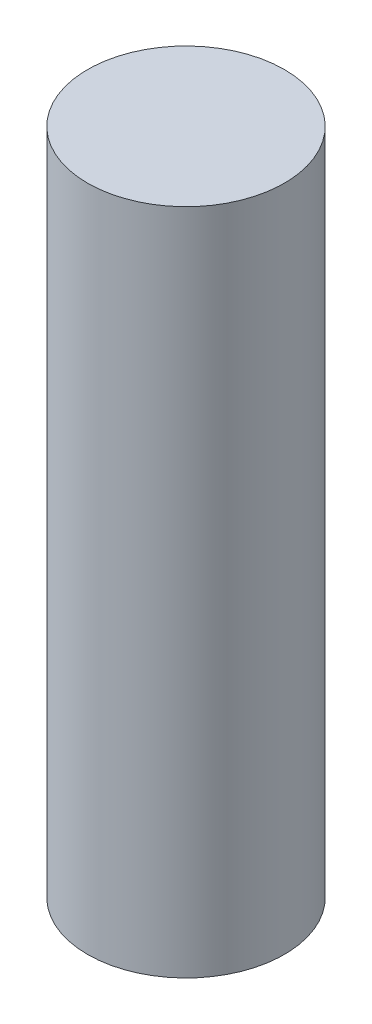
SolidWorks part; units mm, degrees
ref_plane "Front" through (0, 0, 0) normal (0, 0, 1) x (1, 0, 0)
ref_plane "Top" through (0, 0, 0) normal (0, 1, 0) x (1, 0, 0)
ref_plane "Right" through (0, 0, 0) normal (1, 0, 0) x (0, 0, -1)
sketch "Sketch1" plane through (0, 0, 0) normal (0, 1, 0) x (1, 0, 0)
  circle A0 centre (0, 0) radius 1.4
  dimension "D1" = 2.8
extrude "Boss-Extrude1" add sketch "Sketch1" along normal blind 9.5
